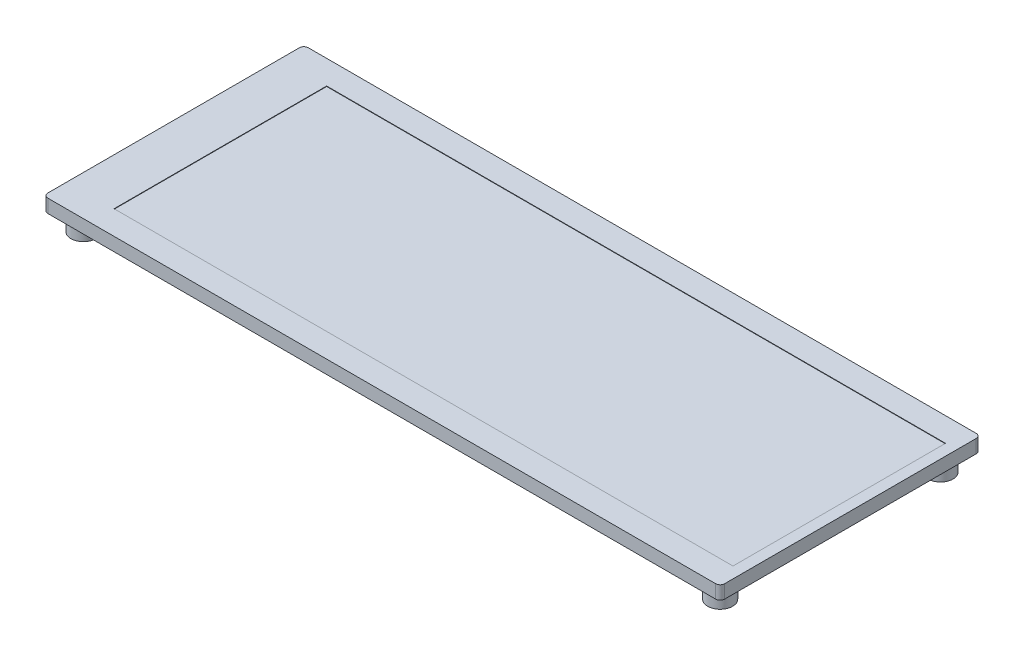
SolidWorks part; units mm, degrees
ref_plane "正面" through (0, 0, 0) normal (0, 0, 1) x (1, 0, 0)
ref_plane "平面" through (0, 0, 0) normal (0, 1, 0) x (1, 0, 0)
ref_plane "右側面" through (0, 0, 0) normal (1, 0, 0) x (0, 0, -1)
sketch "ｽｹｯﾁ1" plane through (0, 0, 0) normal (0, 1, 0) x (1, 0, 0)
  line L1 (-75, 29.25) -> (75, 29.25)
  line L2 (-76, 28.25) -> (-76, -28.25)
  line L3 (-75, -29.25) -> (75, -29.25)
  line L4 (76, 28.25) -> (76, -28.25)
  line L5 (-76, 29.25) -> (76, -29.25) construction
  line L6 (-76, -29.25) -> (76, 29.25) construction
  arc A0 (75, 29.25) -> (76, 28.25) centre (75, 28.25) cw
  arc A1 (-76, -28.25) -> (-75, -29.25) centre (-75, -28.25) ccw
  arc A2 (-75, 29.25) -> (-76, 28.25) centre (-75, 28.25) ccw
  arc A3 (75, -29.25) -> (76, -28.25) centre (75, -28.25) ccw
  point P0 (0, 0)
  dimension "D3" = 1
  dimension "D1" = 58.5
  dimension "D2" = 152
extrude "ﾎﾞｽ - 押し出し1" add sketch "ｽｹｯﾁ1" along normal blind 3
sketch "ｽｹｯﾁ2" plane through (0, 3, 0) normal (0, 1, 0) x (1, 0, 0)
  line L0 (76, -28.25) -> (76, 28.25) construction
  line L1 (-65.5, 23.87) -> (73.5, 23.87)
  line L2 (-65.5, 23.87) -> (-65.5, -23.87)
  line L3 (-65.5, -23.87) -> (73.5, -23.87)
  line L4 (73.5, 23.87) -> (73.5, -23.87)
  line L5 (-65.5, 23.87) -> (73.5, -23.87) construction
  line L6 (-65.5, -23.87) -> (73.5, 23.87) construction
  point P0 (4, 0)
  point P7 (0, 0)
  dimension "D1" = 47.74
  dimension "D2" = 139
  dimension "D3" = 2.5
extrude "ｶｯﾄ - 押し出し1" cut sketch "ｽｹｯﾁ2" against normal blind 0.1
sketch "ｽｹｯﾁ3" plane through (0, 0, 0) normal (0, -1, 0) x (1, 0, 0)
  line L0 (-75, 29.25) -> (75, 29.25) construction
  line L1 (-76, -28.25) -> (-76, 28.25) construction
  circle A0 centre (-71.5, 24.75) radius 2.8
  dimension "D1" = 5.6
  dimension "D2" = 4.5
  dimension "D3" = 4.5
extrude "ﾎﾞｽ - 押し出し2" add sketch "ｽｹｯﾁ3" along normal blind 4
sketch "ｽｹｯﾁ4" plane through (0, -4, 0) normal (0, -1, 0) x (1, 0, 0)
  circle A0 centre (-71.5, 24.75) radius 1
  circle A1 centre (-71.5, 24.75) radius 2.8
  circle A2 centre (-71.5, 24.75) radius 2.8 construction
  dimension "D2" = 2
  dimension "D1" = 0
extrude "ｶｯﾄ - 押し出し2" cut sketch "ｽｹｯﾁ4" against normal blind 4
mirror "ﾐﾗｰ1" about plane through (0, 0, 0) normal (1, 0, 0) of "ﾎﾞｽ - 押し出し2", "ｶｯﾄ - 押し出し2" second plane through (0, 0, 0) second plane normal (0, 0, 1)
sketch "ｽｹｯﾁ5" plane through (0, 0, 0) normal (0, -1, 0) x (1, 0, 0)
  line L0 (-76, -28.25) -> (-76, 28.25) construction
  line L1 (-63, 5.5) -> (-57, 5.5)
  line L2 (-63, 5.5) -> (-63, -5.5)
  line L3 (-63, -5.5) -> (-57, -5.5)
  line L4 (-57, 5.5) -> (-57, -5.5)
  line L5 (-63, 5.5) -> (-57, -5.5) construction
  line L6 (-63, -5.5) -> (-57, 5.5) construction
  point P0 (-60, 0)
  point P7 (0, 0)
  dimension "D1" = 11
  dimension "D2" = 6
  dimension "D3" = 13
extrude "ﾎﾞｽ - 押し出し3" add sketch "ｽｹｯﾁ5" along normal blind 1.7
sketch "ｽｹｯﾁ6" plane through (0, 0, 0) normal (0, -1, 0) x (1, 0, 0)
  line L0 (76, 28.25) -> (76, -28.25) construction
  line L1 (61.5, 8.5) -> (67.5, 8.5)
  line L2 (61.5, 8.5) -> (61.5, -8.5)
  line L3 (61.5, -8.5) -> (67.5, -8.5)
  line L4 (67.5, 8.5) -> (67.5, -8.5)
  line L5 (61.5, 8.5) -> (67.5, -8.5) construction
  line L6 (61.5, -8.5) -> (67.5, 8.5) construction
  point P0 (64.5, 0)
  point P7 (0, 0)
  dimension "D1" = 17
  dimension "D2" = 6
  dimension "D3" = 8.5
extrude "ﾎﾞｽ - 押し出し4" add sketch "ｽｹｯﾁ6" along normal blind 4
